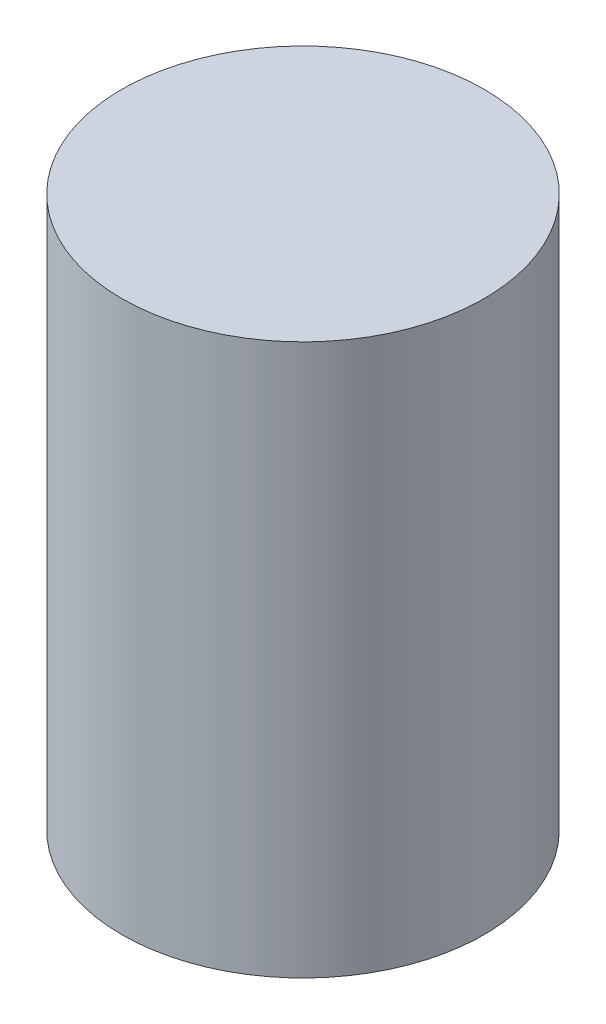
SolidWorks part; units mm, degrees
ref_plane "Front Plane" through (0, 0, 0) normal (0, 0, 1) x (1, 0, 0)
ref_plane "Top Plane" through (0, 0, 0) normal (0, 1, 0) x (1, 0, 0)
ref_plane "Right Plane" through (0, 0, 0) normal (1, 0, 0) x (0, 0, -1)
sketch "Sketch2" plane through (0, 0, 0) normal (0, 1, 0) x (1, 0, 0)
  circle A0 centre (0, 0) radius 76.2
  dimension "D1" = 152.4
extrude "Boss-Extrude1" add sketch "Sketch2" along normal blind 231.648
